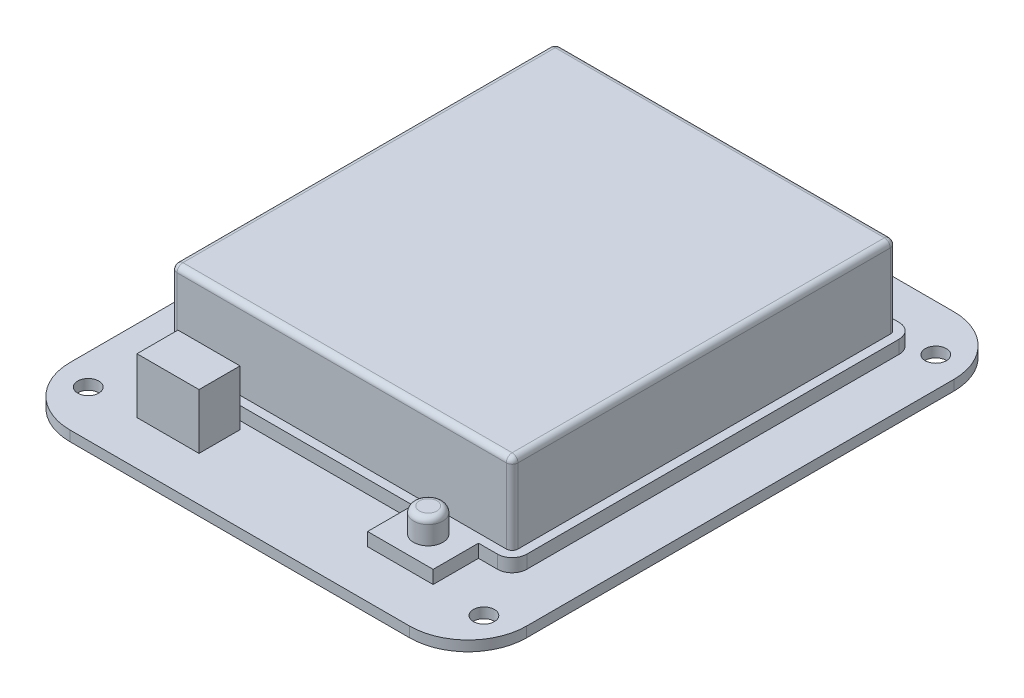
SolidWorks part; units mm, degrees
ref_plane "Front Plane" through (0, 0, 0) normal (0, 0, 1) x (1, 0, 0)
ref_plane "Top Plane" through (0, 0, 0) normal (0, 1, 0) x (1, 0, 0)
ref_plane "Right Plane" through (0, 0, 0) normal (1, 0, 0) x (0, 0, -1)
sketch "Sketch1" plane through (0, 0, 0) normal (0, 1, 0) x (1, 0, 0)
  line L1 (-39, -46.5) -> (39, -46.5)
  line L2 (-39, -46.5) -> (-39, 46.5)
  line L3 (-39, 46.5) -> (39, 46.5)
  line L4 (39, -46.5) -> (39, 46.5)
  point P4 (0, 46.5)
  point P6 (-39, 0)
  point P7 (-39, 20.2934)
  dimension "D1" = 78
  dimension "D2" = 93
extrude "Boss-Extrude1" add sketch "Sketch1" along normal blind 1.75 contours L1 L4 L3 L2
sketch "Sketch2" plane through (0, 1.75, 0) normal (0, 1, 0) x (1, 0, 0)
  line L0 (0, -73.0861) -> (0, 92.8533) construction
  line L1 (-82.586, 0) -> (103.4994, 0) construction
  line L2 (-39, -46.5) -> (-39, 46.5) construction
  line L3 (-39, 46.5) -> (39, 46.5) construction
  line L4 (-39, 36.5) -> (-39, 46.5)
  line L5 (-39, 46.5) -> (-29, 46.5)
  line L6 (39, 36.5) -> (39, 46.5)
  line L7 (39, 46.5) -> (29, 46.5)
  line L8 (39, -36.5) -> (39, -46.5)
  line L9 (39, -46.5) -> (29, -46.5)
  line L10 (-39, -36.5) -> (-39, -46.5)
  line L11 (-39, -46.5) -> (-29, -46.5)
  circle A0 centre (-33.8, 38.6) radius 1.8
  circle A1 centre (33.8, 38.6) radius 1.8
  circle A2 centre (33.8, -38.6) radius 1.8
  circle A3 centre (-33.8, -38.6) radius 1.8
  arc A4 (-39, 36.5) -> (-29, 46.5) centre (-29, 36.5) cw
  arc A5 (39, 36.5) -> (29, 46.5) centre (29, 36.5) ccw
  arc A6 (39, -36.5) -> (29, -46.5) centre (29, -36.5) cw
  arc A7 (-39, -36.5) -> (-29, -46.5) centre (-29, -36.5) ccw
  dimension "D1" = 64
  dimension "D2" = 3.6
  dimension "D3" = 75.4
  dimension "D4" = 10
extrude "Cut-Extrude1" cut sketch "Sketch2" against normal up to surface (1.75 mm away) up to face at (0, 0, 0)
sketch "Sketch3" plane through (0, 1.75, 0) normal (0, 1, 0) x (1, 0, 0)
  line L0 (-29, 46.5) -> (29, 46.5) construction
  line L1 (-29.125, -29.1) -> (29.125, -29.1)
  line L2 (-29.125, -29.1) -> (-29.125, 36.5)
  line L3 (-29.125, 36.5) -> (29.125, 36.5)
  line L4 (29.125, -29.1) -> (29.125, 36.5)
  point P4 (28.6799, 29.8946)
  point P5 (29.4897, 34.6183)
  point P7 (0, 36.5)
  dimension "D1" = 58.25
  dimension "D2" = 65.6
  dimension "D3" = 10
extrude "Boss-Extrude2" add sketch "Sketch3" along normal offset from surface (16 mm away) 17.75 up to face at (33.8, 0, -40.4)
fillet "Fillet1" radius 1 8 edges at (-29.125, 9.75, -36.5) (-29.125, 17.75, -3.7) (0, 17.75, -36.5) (29.125, 9.75, -36.5) (29.125, 17.75, -3.7) (29.125, 9.75, 29.1) (0, 17.75, 29.1) (-29.125, 9.75, 29.1)
sketch "Sketch4" plane through (0, 1.75, 0) normal (0, 1, 0) x (1, 0, 0)
  line L0 (-28.125, -29.1) -> (28.125, -29.1) construction
  line L1 (-25.125, -38.95) -> (-14.525, -38.95)
  line L2 (-25.125, -38.95) -> (-25.125, -31.95)
  line L3 (-25.125, -31.95) -> (-14.525, -31.95)
  line L4 (-14.525, -38.95) -> (-14.525, -31.95)
  line L5 (-29.125, 35.5) -> (-29.125, -28.1) construction
  dimension "D1" = 10.6
  dimension "D2" = 7
  dimension "D3" = 2.85
  dimension "D4" = 4
extrude "Boss-Extrude3" add sketch "Sketch4" along normal offset from surface (9.45 mm away) 11.2 contours L1 L4 L3 L2 up to face at (33.8, 0, -40.4)
sketch "Sketch5" plane through (0, 1.75, 0) normal (0, 1, 0) x (1, 0, 0)
  line L0 (29.125, -28.1) -> (29.125, 35.5) construction
  line L1 (29.125, -28.1) -> (29.125, 35.5)
  line L2 (-29.125, 35.5) -> (-29.125, -28.1) construction
  line L3 (-28.125, -29.1) -> (28.125, -29.1) construction
  line L4 (28.125, 36.5) -> (-28.125, 36.5) construction
  line L5 (-29.125, 35.5) -> (-29.125, -28.1)
  line L6 (-28.125, -29.1) -> (28.125, -29.1)
  line L7 (29.125, -28.1) -> (29.125, 35.5)
  line L8 (28.125, 36.5) -> (-28.125, 36.5)
  line L9 (30.625, -28.1) -> (30.625, 35.5)
  line L10 (28.125, 38) -> (-28.125, 38)
  line L11 (-30.625, 35.5) -> (-30.625, -28.1)
  line L12 (-28.125, -30.6) -> (28.125, -30.6)
  arc A0 (-28.125, 36.5) -> (-29.125, 35.5) centre (-28.125, 35.5) ccw construction
  arc A1 (-29.125, -28.1) -> (-28.125, -29.1) centre (-28.125, -28.1) ccw construction
  arc A2 (28.125, -29.1) -> (29.125, -28.1) centre (28.125, -28.1) ccw construction
  arc A3 (29.125, 35.5) -> (28.125, 36.5) centre (28.125, 35.5) ccw construction
  arc A4 (-28.125, 36.5) -> (-29.125, 35.5) centre (-28.125, 35.5) ccw
  arc A5 (-29.125, -28.1) -> (-28.125, -29.1) centre (-28.125, -28.1) ccw
  arc A6 (28.125, -29.1) -> (29.125, -28.1) centre (28.125, -28.1) ccw
  arc A7 (29.125, 35.5) -> (28.125, 36.5) centre (28.125, 35.5) ccw
  arc A8 (30.625, 35.5) -> (28.125, 38) centre (28.125, 35.5) ccw
  arc A9 (-28.125, 38) -> (-30.625, 35.5) centre (-28.125, 35.5) ccw
  arc A10 (-30.625, -28.1) -> (-28.125, -30.6) centre (-28.125, -28.1) ccw
  arc A11 (28.125, -30.6) -> (30.625, -28.1) centre (28.125, -28.1) ccw
  line M19 (-28.125, 36.5) -> (28.125, 36.5)
  arc M20 (28.125, 36.5) -> (29.125, 35.5) centre (28.125, 35.5) cw
  line M21 (29.125, 35.5) -> (29.125, -28.1)
  arc M22 (29.125, -28.1) -> (28.125, -29.1) centre (28.125, -28.1) cw
  line M23 (28.125, -29.1) -> (-28.125, -29.1)
  arc M24 (-28.125, -29.1) -> (-29.125, -28.1) centre (-28.125, -28.1) cw
  line M25 (-29.125, -28.1) -> (-29.125, 35.5)
  arc M26 (-29.125, 35.5) -> (-28.125, 36.5) centre (-28.125, 35.5) cw
  dimension "D1" = 1.5
extrude "Boss-Extrude4" add sketch "Sketch5" along normal offset from surface (2.25 mm away) 4 contours L12 A11 L9 A8 L10 A9 L11 A10 M26 M19 M20 M21 M22 M23 M24 M25 up to face at (33.8, 0, -40.4)
sketch "Sketch6" plane through (0, 1.75, 0) normal (0, 1, 0) x (1, 0, 0)
  line L0 (-28.125, -30.6) -> (28.125, -30.6) construction
  line L1 (13.675, -30.6) -> (24.875, -30.6)
  line L2 (13.675, -30.6) -> (13.675, -38.35)
  line L3 (13.675, -38.35) -> (24.875, -38.35)
  line L4 (24.875, -30.6) -> (24.875, -38.35)
  line L5 (-28.125, -29.1) -> (28.125, -29.1) construction
  line L6 (30.625, -28.1) -> (30.625, 35.5) construction
  dimension "D1" = 9.25
  dimension "D2" = 11.2
  dimension "D3" = 5.75
extrude "Boss-Extrude5" add sketch "Sketch6" along normal up to surface (2.25 mm away) contours L3 L4 L1 L2 up to face at (0, 4, -3.7)
sketch "Sketch7" plane through (0, 0, 0) normal (0, -1, 0) x (1, 0, 0)
  line L8 (25.625, 25.6) -> (-25.625, 25.6)
  line L9 (25.625, -33) -> (25.625, 25.6)
  line L10 (-25.625, -33) -> (25.625, -33)
  line L11 (-25.625, 25.6) -> (-25.625, -33)
  line L12 (25.625, 25.6) -> (-25.625, 25.6)
  line L13 (25.625, -33) -> (25.625, 25.6)
  line L14 (-25.625, -33) -> (25.625, -33)
  line L15 (-25.625, 25.6) -> (-25.625, -33)
  dimension "D1" = 2.5
extrude "Cut-Extrude2" cut sketch "Sketch7" against normal offset from surface (13.75 mm away) 4 up to face at (0, 17.75, -3.7)
sketch "Sketch8" plane through (0, 4, 0) normal (0, 1, 0) x (1, 0, 0)
  circle A0 centre (19.2226, -33.5365) radius 2.5
  dimension "D1" = 5
extrude "Boss-Extrude6" add sketch "Sketch8" along direction (0, -1, 0) on the side of the normal offset from surface (4.15 mm away) 8.15
fillet "Fillet2" radius 1 1 edges at (19.2226, 8.15, 31.0365)
